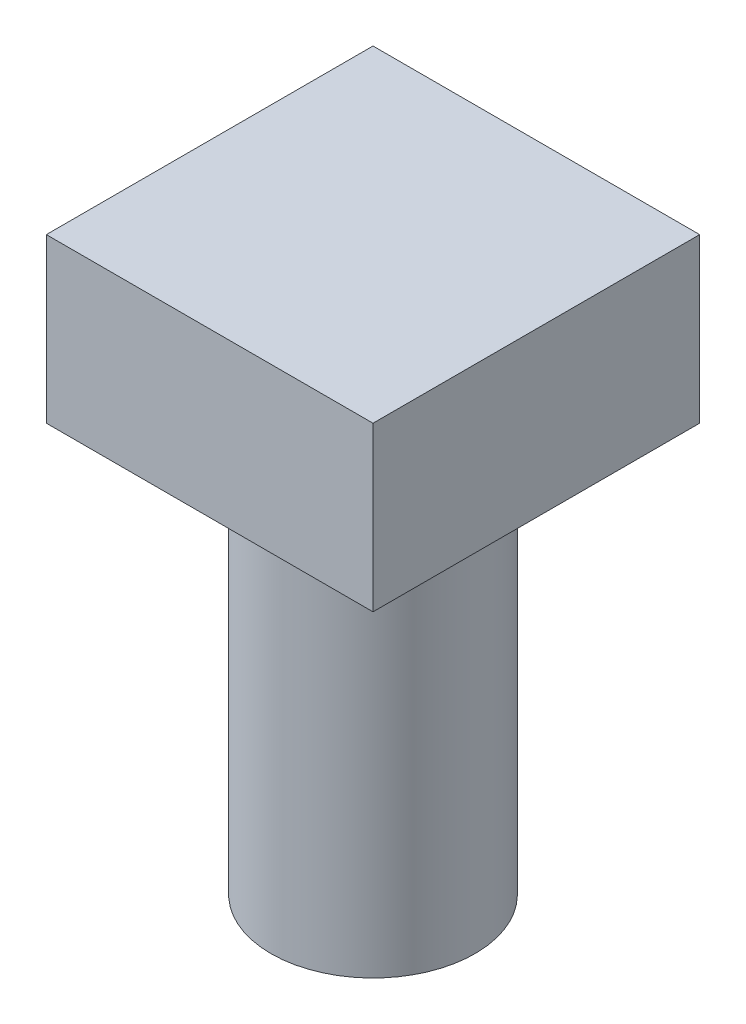
SolidWorks part; units mm, degrees
ref_plane "Front Plane" through (0, 0, 0) normal (0, 0, 1) x (1, 0, 0)
ref_plane "Top Plane" through (0, 0, 0) normal (0, 1, 0) x (1, 0, 0)
ref_plane "Right Plane" through (0, 0, 0) normal (1, 0, 0) x (0, 0, -1)
sketch "Sketch1" plane through (0, 0, 0) normal (0, 1, 0) x (1, 0, 0)
  circle A0 centre (0, 0) radius 3.175
  dimension "D1" = 6.35
extrude "Boss-Extrude1" add sketch "Sketch1" along normal blind 12.7
sketch "Sketch2" plane through (0, 12.7, 0) normal (0, 1, 0) x (1, 0, 0)
  line L1 (-5.08, -5.08) -> (5.08, -5.08)
  line L2 (-5.08, -5.08) -> (-5.08, 5.08)
  line L3 (-5.08, 5.08) -> (5.08, 5.08)
  line L4 (5.08, -5.08) -> (5.08, 5.08)
  line L5 (-5.08, -5.08) -> (5.08, 5.08) construction
  line L6 (-5.08, 5.08) -> (5.08, -5.08) construction
  point P0 (0, 0)
  dimension "D1" = 10.16
  dimension "D2" = 10.16
extrude "Boss-Extrude2" add sketch "Sketch2" along normal blind 5.08
